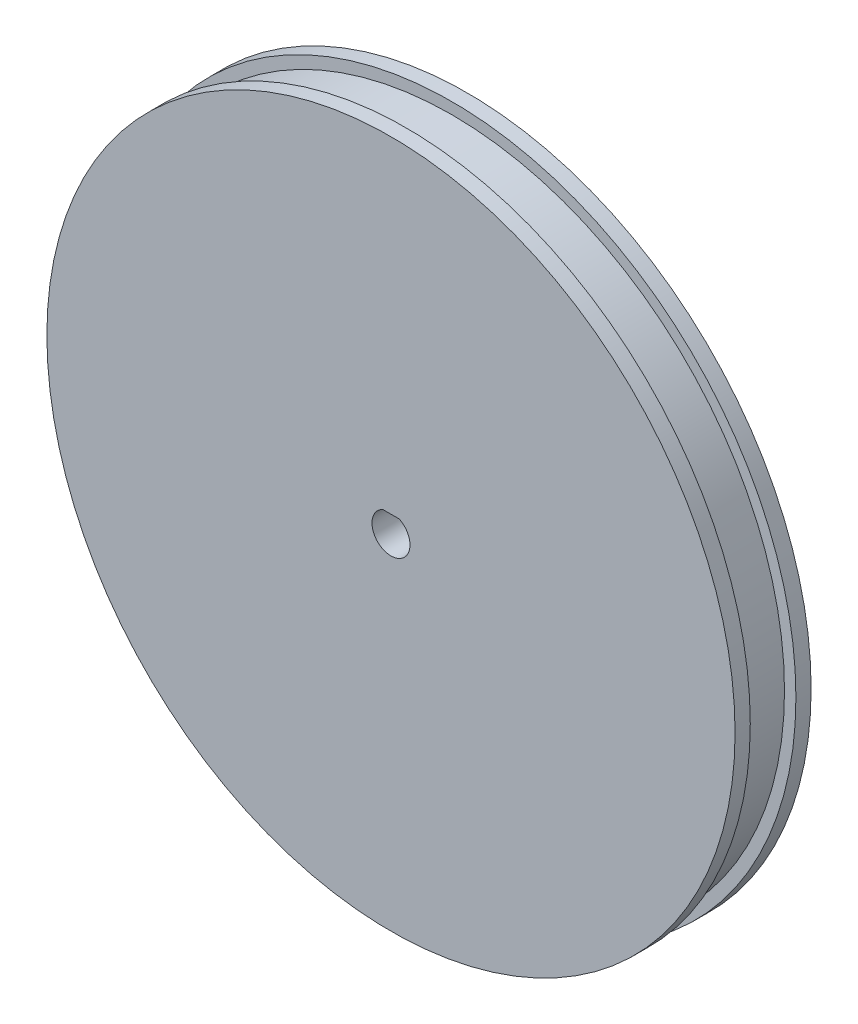
SolidWorks part; units mm, degrees
ref_plane "Vorne" through (0, 0, 0) normal (0, 0, 1) x (1, 0, 0)
ref_plane "Oben" through (0, 0, 0) normal (0, 1, 0) x (1, 0, 0)
ref_plane "Rechts" through (0, 0, 0) normal (1, 0, 0) x (0, 0, -1)
ref_plane "E_Boden" through (0, 1, 0) normal (0, 1, 0) x (1, 0, 0)
sketch "Skizze2" plane through (0, 0, 0) normal (0, 0, 1) x (1, 0, 0)
  circle A0 centre (0, 0) radius 43.75
  dimension "D1" = 87.5
extrude "Zahnfläche" add sketch "Skizze2" along normal blind 6
sketch "Skizze4" plane through (0, 0, 0) normal (0, 0, -1) x (-1, 0, 0)
  circle A0 centre (0, 0) radius 45.25
  dimension "D1" = 90.5
extrude "Seitenteil1" add sketch "Skizze4" along normal blind 2
sketch "Skizze5" plane through (0, 0, 6) normal (0, 0, 1) x (1, 0, 0)
  circle A0 centre (0, 0) radius 45.25
  dimension "D1" = 90.5
extrude "Seitenteil2" add sketch "Skizze5" along normal blind 2
sketch "Skizze6" plane through (0, 0, 8) normal (0, 0, 1) x (1, 0, 0)
  line L0 (0, 45.25) -> (0, -45.25) construction
  line L1 (-45.25, 0) -> (45.25, 0) construction
  line L2 (-20.7727, 2.25) -> (23.9017, 2.25) construction
  line L3 (-1.0897, 2.25) -> (1.0897, 2.25)
  circle A0 centre (0, 0) radius 45.25 construction
  arc A1 (-1.0897, 2.25) -> (1.0897, 2.25) centre (0, 0) ccw
  dimension "D2" = 2.5
  dimension "D1" = 2.25
extrude "Aussparung" cut sketch "Skizze6" against normal through all
